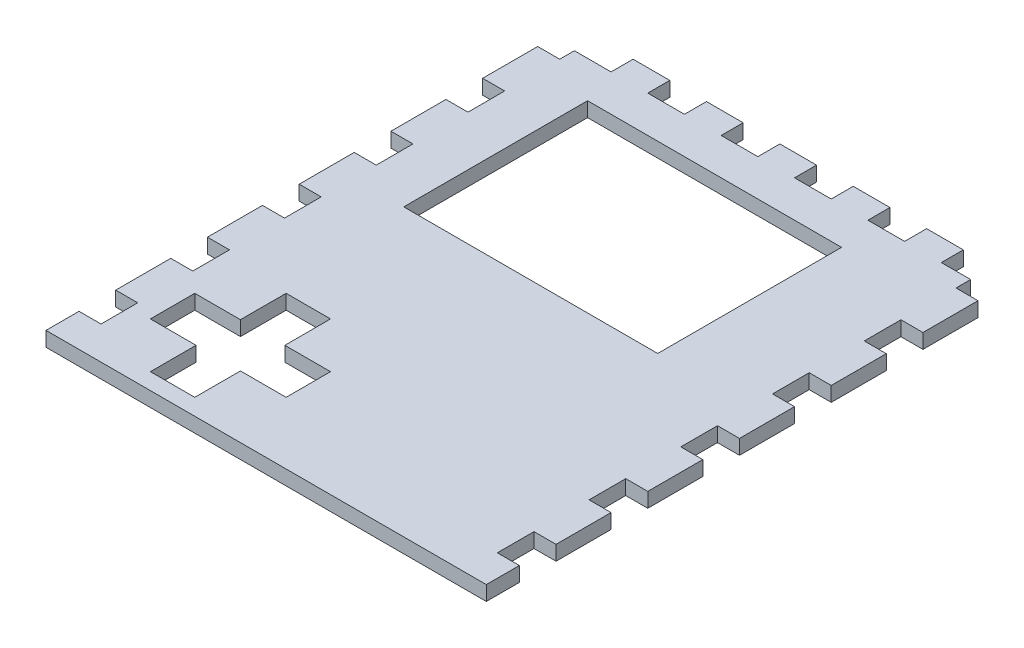
SolidWorks part; units mm, degrees
ref_plane "Спереди" through (0, 0, 0) normal (0, 0, 1) x (1, 0, 0)
ref_plane "Сверху" through (0, 0, 0) normal (0, 1, 0) x (1, 0, 0)
ref_plane "Справа" through (0, 0, 0) normal (1, 0, 0) x (0, 0, -1)
other "Configuration Table"
sketch "Эскиз1" plane through (0, 0, 0) normal (0, 1, 0) x (1, 0, 0)
  line L1 (0, 0) -> (108, 0)
  line L2 (0, 0) -> (0, -138)
  line L3 (0, -138) -> (108, -138)
  line L4 (108, 0) -> (108, -138)
  dimension "D1" = 138
  dimension "D2" = 108
extrude "Бобышка-Вытянуть1" add sketch "Эскиз1" along normal blind 4
sketch "Эскиз2" plane through (0, 4, 0) normal (0, 1, 0) x (1, 0, 0)
  line L0 (0, 0) -> (0, -138) construction
  line L1 (13.6, -10) -> (82.81, -10)
  line L2 (13.6, -10) -> (13.6, -60.1)
  line L3 (13.6, -60.1) -> (82.81, -60.1)
  line L4 (82.81, -10) -> (82.81, -60.1)
  line L6 (108, 0) -> (0, 0) construction
  dimension "D1" = 50.1
  dimension "D2" = 69.21
  dimension "D3" = 13.6
  dimension "D4" = 10
extrude "Вырез-Вытянуть1" cut sketch "Эскиз2" against normal through all
sketch "Эскиз3" plane through (0, 4, 0) normal (0, 1, 0) x (1, 0, 0)
  line L0 (0, -138) -> (108, -138) construction
  line L1 (17.9723, -96.5301) -> (30.0723, -96.5301)
  line L2 (17.9723, -96.5301) -> (17.9723, -133.5301)
  line L3 (17.9723, -133.5301) -> (30.0723, -133.5301)
  line L4 (30.0723, -96.5301) -> (30.0723, -133.5301)
  line L5 (0, 0) -> (0, -138) construction
  line L7 (5.5223, -121.0801) -> (42.5223, -121.0801)
  line L8 (5.5223, -121.0801) -> (5.5223, -108.9801)
  line L9 (5.5223, -108.9801) -> (42.5223, -108.9801)
  line L10 (42.5223, -121.0801) -> (42.5223, -108.9801)
  dimension "D1" = 12.1
  dimension "D2" = 37
  dimension "D3" = 4.4699
  dimension "D4" = 17.9723
  dimension "D5" = 12.1
  dimension "D6" = 37
  dimension "D7" = 12.45
  dimension "D8" = 12.45
extrude "Вырез-Вытянуть2" cut sketch "Эскиз3" against normal through all contours L9 L2 L7 L4 | L2 L9 L4 L1 | L9 L8 L7 L2 | L7 L10 L9 L4 | L7 L2 L3 L4
sketch "Эскиз4" plane through (0, 0, 0) normal (-1, 0, 0) x (0, 0, 1)
  line L0 (0, 4) -> (138, 4) construction
  line L1 (4, 4) -> (19, 4)
  line L2 (4, 4) -> (4, 0)
  line L3 (4, 0) -> (19, 0)
  line L4 (19, 4) -> (19, 0)
  line L5 (0, 0) -> (138, 0) construction
  line L6 (0, 4) -> (0, 0) construction
  line L7 (29, 4) -> (29, 0)
  line L8 (29, 4) -> (44, 4)
  line L9 (44, 4) -> (44, 0)
  line L10 (29, 0) -> (44, 0)
  line L11 (54, 4) -> (54, 0)
  line L12 (54, 4) -> (69, 4)
  line L13 (69, 4) -> (69, 0)
  line L14 (54, 0) -> (69, 0)
  line L15 (79, 4) -> (79, 0)
  line L16 (79, 4) -> (94, 4)
  line L17 (94, 4) -> (94, 0)
  line L18 (79, 0) -> (94, 0)
  line L19 (104, 4) -> (104, 0)
  line L20 (104, 4) -> (119, 4)
  line L21 (119, 4) -> (119, 0)
  line L22 (104, 0) -> (119, 0)
  dimension "D1" = 15
  dimension "D2" = 4
  dimension "D3" = 5
extrude "Бобышка-Вытянуть2" add sketch "Эскиз4" along normal blind 6
sketch "Эскиз5" plane through (0, 4, 0) normal (0, 1, 0) x (1, 0, 0)
  line L0 (54, 0) -> (54, -138) construction
  line L1 (108, 0) -> (0, 0) construction
  line L2 (0, -138) -> (108, -138) construction
sketch "Эскиз6" plane through (0, 0, 0) normal (-1, 0, 0) x (0, 0, 1)
  line L0 (119, 0) -> (138, 0) construction
  line L1 (138, 4) -> (129, 4)
  line L2 (138, 4) -> (138, 0)
  line L3 (138, 0) -> (129, 0)
  line L4 (129, 4) -> (129, 0)
  line L5 (119, 0) -> (119, 4) construction
  dimension "D1" = 10
extrude "Бобышка-Вытянуть3" add sketch "Эскиз6" along normal blind 6
sketch "Эскиз7" plane through (108, 0, 0) normal (1, 0, 0) x (0, 0, -1)
  line L0 (-138, 0) -> (0, 0) construction
  line L1 (-4, 4) -> (-19, 4)
  line L2 (-4, 4) -> (-4, 0)
  line L3 (-4, 0) -> (-19, 0)
  line L4 (-19, 4) -> (-19, 0)
  line L5 (-29, 4) -> (-29, 0)
  line L6 (-29, 4) -> (-44, 4)
  line L7 (-44, 4) -> (-44, 0)
  line L8 (-29, 0) -> (-44, 0)
  line L9 (-54, 4) -> (-54, 0)
  line L10 (-54, 4) -> (-69, 4)
  line L11 (-69, 4) -> (-69, 0)
  line L12 (-54, 0) -> (-69, 0)
  line L13 (-79, 4) -> (-79, 0)
  line L14 (-79, 4) -> (-94, 4)
  line L15 (-94, 4) -> (-94, 0)
  line L16 (-79, 0) -> (-94, 0)
  line L17 (-104, 4) -> (-104, 0)
  line L18 (-104, 4) -> (-119, 4)
  line L19 (-119, 4) -> (-119, 0)
  line L20 (-104, 0) -> (-119, 0)
  dimension "D1" = 15
  dimension "D2" = 5
extrude "Бобышка-Вытянуть4" add sketch "Эскиз7" along normal blind 6
sketch "Эскиз8" plane through (108, 0, 0) normal (1, 0, 0) x (0, 0, -1)
  line L0 (-138, 0) -> (-119, 0) construction
  line L1 (-138, 4) -> (-129, 4)
  line L2 (-138, 4) -> (-138, 0)
  line L3 (-138, 0) -> (-129, 0)
  line L4 (-129, 4) -> (-129, 0)
  dimension "D1" = 9
extrude "Бобышка-Вытянуть5" add sketch "Эскиз8" along normal blind 6
sketch "Эскиз9" plane through (0, 0, 0) normal (0, 0, -1) x (-1, 0, 0)
  line L0 (-108, 4) -> (0, 4) construction
  line L1 (-99.9985, 4) -> (-89.9985, 4)
  line L2 (-99.9985, 4) -> (-99.9985, 0)
  line L3 (-99.9985, 0) -> (-89.9985, 0)
  line L4 (-89.9985, 4) -> (-89.9985, 0)
  line L5 (-108, 0) -> (0, 0) construction
  line L6 (-108, 4) -> (-108, 0) construction
  line L7 (-79.9985, 4) -> (-79.9985, 0)
  line L8 (-79.9985, 4) -> (-69.9985, 4)
  line L9 (-69.9985, 4) -> (-69.9985, 0)
  line L10 (-79.9985, 0) -> (-69.9985, 0)
  line L11 (-59.9985, 4) -> (-59.9985, 0)
  line L12 (-59.9985, 4) -> (-49.9985, 4)
  line L13 (-49.9985, 4) -> (-49.9985, 0)
  line L14 (-59.9985, 0) -> (-49.9985, 0)
  line L15 (-39.9985, 4) -> (-39.9985, 0)
  line L16 (-39.9985, 4) -> (-29.9985, 4)
  line L17 (-29.9985, 4) -> (-29.9985, 0)
  line L18 (-39.9985, 0) -> (-29.9985, 0)
  line L19 (-19.9985, 4) -> (-19.9985, 0)
  line L20 (-19.9985, 4) -> (-9.9985, 4)
  line L21 (-9.9985, 4) -> (-9.9985, 0)
  line L22 (-19.9985, 0) -> (-9.9985, 0)
  dimension "D1" = 10
  dimension "D2" = 8.0015
  dimension "D3" = 5
extrude "Бобышка-Вытянуть6" add sketch "Эскиз9" along normal blind 6
